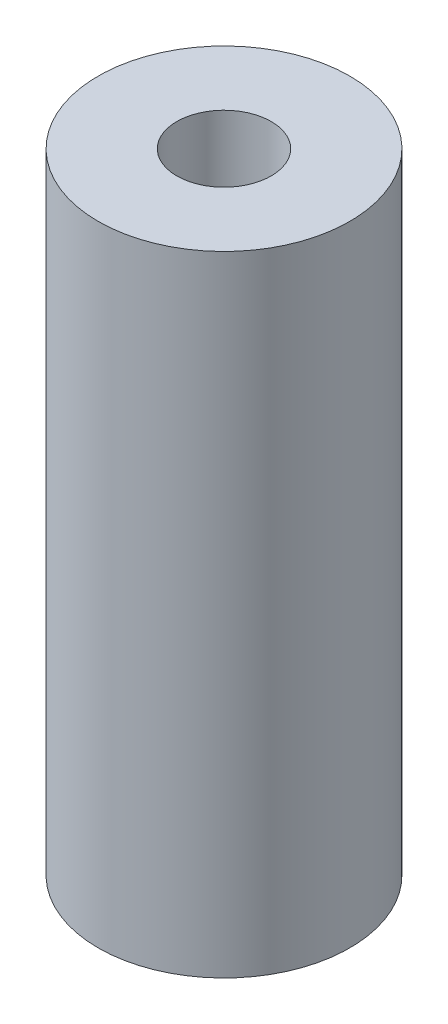
SolidWorks part; units mm, degrees
ref_plane "Спереди" through (0, 0, 0) normal (0, 0, 1) x (1, 0, 0)
ref_plane "Сверху" through (0, 0, 0) normal (0, 1, 0) x (1, 0, 0)
ref_plane "Справа" through (0, 0, 0) normal (1, 0, 0) x (0, 0, -1)
sketch "Эскиз1" plane through (0, 0, 0) normal (0, 1, 0) x (1, 0, 0)
  circle A0 centre (0, 0) radius 6
  circle A1 centre (0, 0) radius 2.25
  dimension "D1" = 4.5
  dimension "D2" = 12
extrude "Бобышка-Вытянуть1" add sketch "Эскиз1" along normal blind 30
